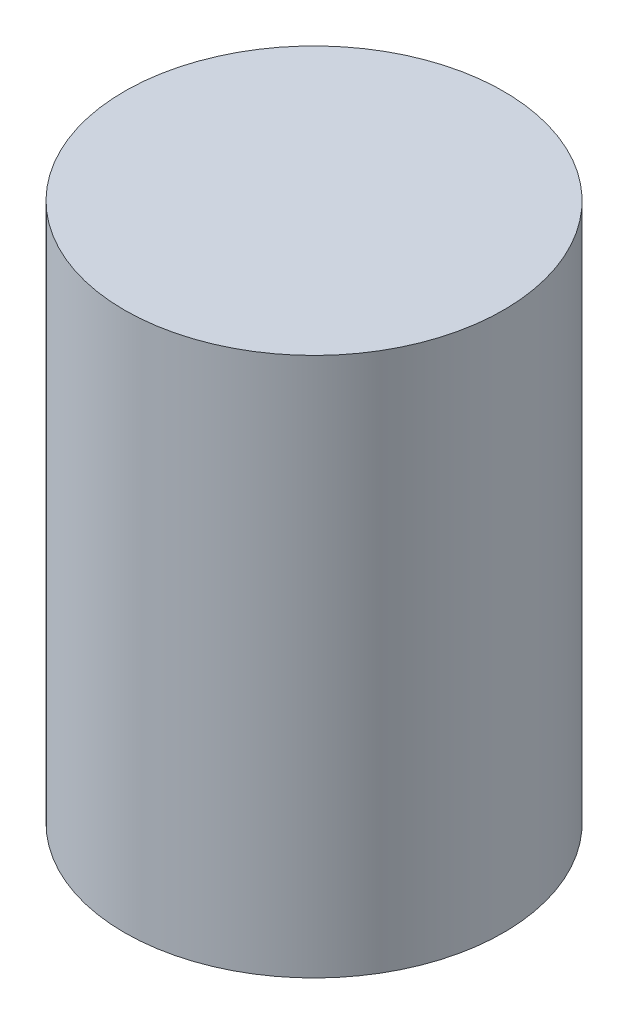
SolidWorks part; units mm, degrees
ref_plane "Alzado" through (0, 0, 0) normal (0, 0, 1) x (1, 0, 0)
ref_plane "Planta" through (0, 0, 0) normal (0, 1, 0) x (1, 0, 0)
ref_plane "Vista lateral" through (0, 0, 0) normal (1, 0, 0) x (0, 0, -1)
sketch "Sketch1" plane through (0, 0, 0) normal (0, 1, 0) x (1, 0, 0)
  circle A0 centre (0, 0) radius 11.25
  dimension "D1" = 22.5
extrude "Boss-Extrude1" add sketch "Sketch1" along normal blind 32
ref_plane "Plane4" through (0, 0, 15) normal (0, 0, 1) x (1, 0, 0)
sketch "Sketch2" plane through (0, 0, 15) normal (0, 0, 1) x (1, 0, 0)
  circle A0 centre (-0.951, 16.766) radius 1.5849
